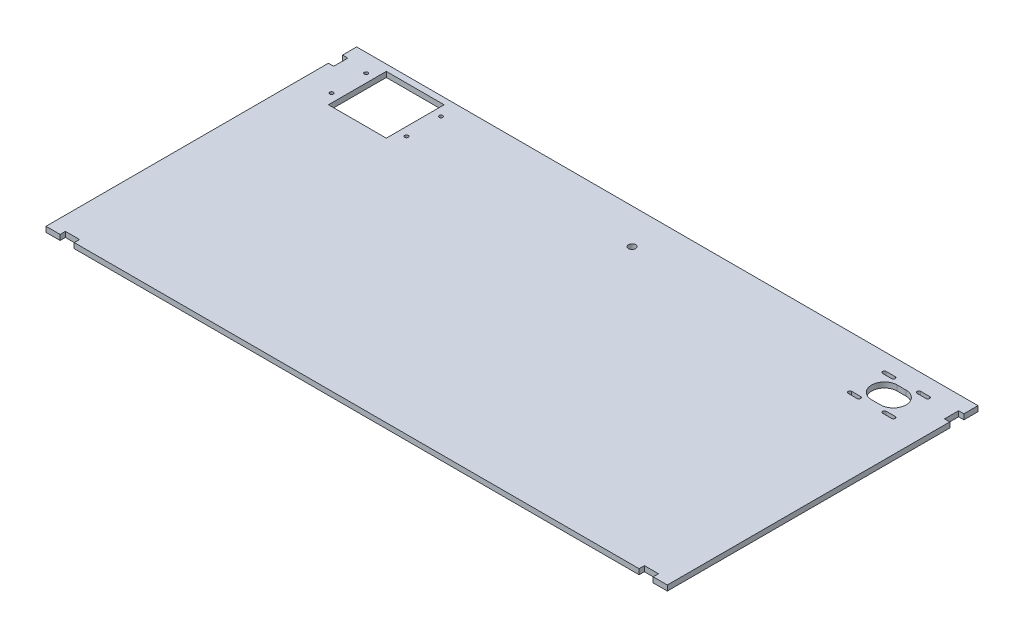
SolidWorks part; units mm, degrees
ref_plane "Front" through (0, 0, 0) normal (0, 0, 1) x (1, 0, 0)
ref_plane "Top" through (0, 0, 0) normal (0, 1, 0) x (1, 0, 0)
ref_plane "Right" through (0, 0, 0) normal (1, 0, 0) x (0, 0, -1)
sketch "Sketch1" plane through (0, 0, 0) normal (0, 1, 0) x (1, 0, 0)
  line L0 (279.4, 247.65) -> (279.4, 279.4) construction
  line L1 (0, 0) -> (12.7, 0)
  line L2 (0, 0) -> (0, 254)
  line L3 (0, 279.4) -> (558.8, 279.4)
  line L4 (558.8, 0) -> (558.8, 254)
  line L5 (38.9, 263.15) -> (46.9, 263.15) construction
  line L6 (38.9, 264.75) -> (46.9, 264.75)
  line L7 (0, 254) -> (4.7625, 254)
  line L8 (558.8, 266.7) -> (554.0375, 266.7)
  line L10 (558.8, 254) -> (554.0375, 254)
  line L11 (554.0375, 266.7) -> (554.0375, 254)
  line L12 (4.7625, 266.7) -> (4.7625, 254)
  line L13 (0, 266.7) -> (4.7625, 266.7)
  line L15 (558.8, 266.7) -> (558.8, 279.4)
  line L16 (0, 266.7) -> (0, 279.4)
  line L17 (25.4, 0) -> (533.4, 0)
  line L19 (12.7, 0) -> (12.7, 4.7625)
  line L20 (12.7, 4.7625) -> (25.4, 4.7625)
  line L21 (25.4, 0) -> (25.4, 4.7625)
  line L22 (533.4, 0) -> (533.4, 4.7625)
  line L23 (546.1, 4.7625) -> (533.4, 4.7625)
  line L24 (546.1, 0) -> (546.1, 4.7625)
  line L25 (546.1, 0) -> (558.8, 0)
  line L26 (58.4, 247.65) -> (279.4, 247.65) construction
  line L27 (42.9, 263.15) -> (73.9, 263.15) construction
  line L28 (42.9, 263.15) -> (42.9, 232.15) construction
  line L29 (42.9, 232.15) -> (73.9, 232.15) construction
  line L30 (73.9, 263.15) -> (73.9, 232.15) construction
  line L31 (42.9, 263.15) -> (73.9, 232.15) construction
  line L32 (42.9, 232.15) -> (73.9, 263.15) construction
  line L33 (494.9, 263.15) -> (525.9, 263.15) construction
  line L34 (494.9, 263.15) -> (494.9, 232.15) construction
  line L35 (494.9, 232.15) -> (525.9, 232.15) construction
  line L36 (525.9, 263.15) -> (525.9, 232.15) construction
  line L37 (494.9, 263.15) -> (525.9, 232.15) construction
  line L38 (494.9, 232.15) -> (525.9, 263.15) construction
  line L39 (279.4, 247.65) -> (510.4, 247.65) construction
  line L40 (38.9, 261.55) -> (46.9, 261.55)
  line L41 (69.9, 263.15) -> (77.9, 263.15) construction
  line L42 (69.9, 264.75) -> (77.9, 264.75)
  line L43 (69.9, 261.55) -> (77.9, 261.55)
  line L44 (38.9, 232.15) -> (46.9, 232.15) construction
  line L45 (38.9, 233.75) -> (46.9, 233.75)
  line L46 (38.9, 230.55) -> (46.9, 230.55)
  line L47 (69.9, 232.15) -> (77.9, 232.15) construction
  line L48 (69.9, 233.75) -> (77.9, 233.75)
  line L49 (69.9, 230.55) -> (77.9, 230.55)
  line L50 (490.9, 263.15) -> (498.9, 263.15) construction
  line L51 (490.9, 264.75) -> (498.9, 264.75)
  line L52 (490.9, 261.55) -> (498.9, 261.55)
  line L53 (490.9, 232.15) -> (498.9, 232.15) construction
  line L54 (490.9, 233.75) -> (498.9, 233.75)
  line L55 (490.9, 230.55) -> (498.9, 230.55)
  line L56 (521.9, 232.15) -> (529.9, 232.15) construction
  line L57 (521.9, 233.75) -> (529.9, 233.75)
  line L58 (521.9, 230.55) -> (529.9, 230.55)
  line L59 (529.9, 263.15) -> (521.9, 263.15) construction
  line L60 (529.9, 261.55) -> (521.9, 261.55)
  line L61 (529.9, 264.75) -> (521.9, 264.75)
  line L62 (54.4, 247.65) -> (62.4, 247.65) construction
  line L63 (54.4, 259.15) -> (62.4, 259.15)
  line L64 (54.4, 236.15) -> (62.4, 236.15)
  line L65 (506.4, 247.65) -> (514.4, 247.65) construction
  line L66 (506.4, 259.15) -> (514.4, 259.15)
  line L67 (506.4, 236.15) -> (514.4, 236.15)
  circle A0 centre (279.4, 247.65) radius 3.175
  arc A12 (38.9, 264.75) -> (38.9, 261.55) centre (38.9, 263.15) ccw
  arc A13 (46.9, 261.55) -> (46.9, 264.75) centre (46.9, 263.15) ccw
  arc A14 (69.9, 264.75) -> (69.9, 261.55) centre (69.9, 263.15) ccw
  arc A15 (77.9, 261.55) -> (77.9, 264.75) centre (77.9, 263.15) ccw
  arc A16 (38.9, 233.75) -> (38.9, 230.55) centre (38.9, 232.15) ccw
  arc A17 (46.9, 230.55) -> (46.9, 233.75) centre (46.9, 232.15) ccw
  arc A18 (69.9, 233.75) -> (69.9, 230.55) centre (69.9, 232.15) ccw
  arc A19 (77.9, 230.55) -> (77.9, 233.75) centre (77.9, 232.15) ccw
  arc A20 (490.9, 264.75) -> (490.9, 261.55) centre (490.9, 263.15) ccw
  arc A21 (498.9, 261.55) -> (498.9, 264.75) centre (498.9, 263.15) ccw
  arc A22 (490.9, 233.75) -> (490.9, 230.55) centre (490.9, 232.15) ccw
  arc A23 (498.9, 230.55) -> (498.9, 233.75) centre (498.9, 232.15) ccw
  arc A24 (521.9, 233.75) -> (521.9, 230.55) centre (521.9, 232.15) ccw
  arc A25 (529.9, 230.55) -> (529.9, 233.75) centre (529.9, 232.15) ccw
  arc A26 (529.9, 261.55) -> (529.9, 264.75) centre (529.9, 263.15) ccw
  arc A27 (521.9, 264.75) -> (521.9, 261.55) centre (521.9, 263.15) ccw
  arc A28 (54.4, 259.15) -> (54.4, 236.15) centre (54.4, 247.65) ccw
  arc A29 (62.4, 236.15) -> (62.4, 259.15) centre (62.4, 247.65) ccw
  arc A30 (506.4, 259.15) -> (506.4, 236.15) centre (506.4, 247.65) ccw
  arc A31 (514.4, 236.15) -> (514.4, 259.15) centre (514.4, 247.65) ccw
  point P19 (73.9, 263.15)
  point P24 (42.9, 263.15)
  point P32 (494.9, 232.15)
  point P44 (12.7, 2.3813)
  point P57 (42.9, 232.15)
  point P64 (73.9, 232.15)
  point P70 (494.9, 263.15)
  point P80 (525.9, 232.15)
  point P87 (525.9, 263.15)
  point P95 (58.4, 247.65)
  point P100 (510.4, 247.65)
  dimension "D4" = 6.35
  dimension "D5" = 1.6
  dimension "D10" = 4
  dimension "D3" = 31.75
  dimension "D9" = 11.5
  dimension "D1" = 279.4
  dimension "D2" = 558.8
  dimension "D6" = 221
  dimension "D7" = 231
  dimension "D8" = 31
  dimension "D11" = 4
  dimension "D12" = 4.7625
  dimension "D13" = 12.7
  dimension "D14" = 12.7
  dimension "D15" = 4.7625
  dimension "D16" = 12.7
  dimension "D17" = 12.7
  dimension "D18" = 12.7
  dimension "D19" = 12.7
extrude "Boss-Extrude1" add sketch "Sketch1" along normal blind 4.7625
sketch "Sketch5" plane through (0, 4.7625, 0) normal (0, 1, 0) x (1, 0, 0)
  line L0 (510.4, 259.15) -> (510.4, 236.15) construction
  line L5 (514.4, 259.15) -> (506.4, 259.15) construction
  line L6 (506.4, 236.15) -> (514.4, 236.15) construction
  line L7 (494.9, 247.65) -> (525.9, 247.65) construction
  line L16 (58.4, 259.15) -> (58.4, 236.15) construction
  line L23 (62.4, 259.15) -> (54.4, 259.15) construction
  line L24 (54.4, 236.15) -> (62.4, 236.15) construction
  line L25 (42.9, 247.65) -> (73.9, 247.65) construction
  line L26 (37.3, 232.15) -> (48.5, 232.15) construction
  line L27 (32.4, 221.65) -> (84.4, 221.65)
  line L28 (32.4, 221.65) -> (32.4, 273.65)
  line L29 (32.4, 273.65) -> (84.4, 273.65)
  line L30 (84.4, 221.65) -> (84.4, 273.65)
  line L31 (32.4, 221.65) -> (84.4, 273.65) construction
  line L32 (32.4, 273.65) -> (84.4, 221.65) construction
  line L33 (17.125, 224.536) -> (99.675, 224.536) construction
  line L34 (17.125, 224.536) -> (17.125, 270.764) construction
  line L35 (17.125, 270.764) -> (99.675, 270.764) construction
  line L36 (99.675, 224.536) -> (99.675, 270.764) construction
  line L37 (17.125, 224.536) -> (99.675, 270.764) construction
  line L38 (17.125, 270.764) -> (99.675, 224.536) construction
  arc A0 (506.4, 259.15) -> (506.4, 236.15) centre (506.4, 247.65) ccw construction
  arc A1 (514.4, 236.15) -> (514.4, 259.15) centre (514.4, 247.65) ccw construction
  arc A6 (54.4, 259.15) -> (54.4, 236.15) centre (54.4, 247.65) ccw construction
  arc A9 (62.4, 236.15) -> (62.4, 259.15) centre (62.4, 247.65) ccw construction
  circle A10 centre (24.745, 263.144) radius 1.5875
  circle A11 centre (24.745, 232.15) radius 1.5875
  circle A12 centre (92.055, 263.144) radius 1.5875
  circle A13 centre (92.055, 232.15) radius 1.5875
  arc A14 (38.9, 233.75) -> (38.9, 230.55) centre (38.9, 232.15) ccw construction
  arc A15 (46.9, 230.55) -> (46.9, 233.75) centre (46.9, 232.15) ccw construction
  point P0 (510.4, 247.65)
  point P1 (0, 0)
  point P33 (510.4, 247.65)
  point P55 (58.4, 247.65)
  point P60 (58.4, 247.65)
  dimension "D2" = 3.175
  dimension "D8" = 7.62
  dimension "D9" = 7.62
  dimension "D3" = 82.55
  dimension "D4" = 46.228
  dimension "D7" = 52
  dimension "D10" = 7.62
extrude "Cut-Extrude2" cut sketch "Sketch5" against normal through all
